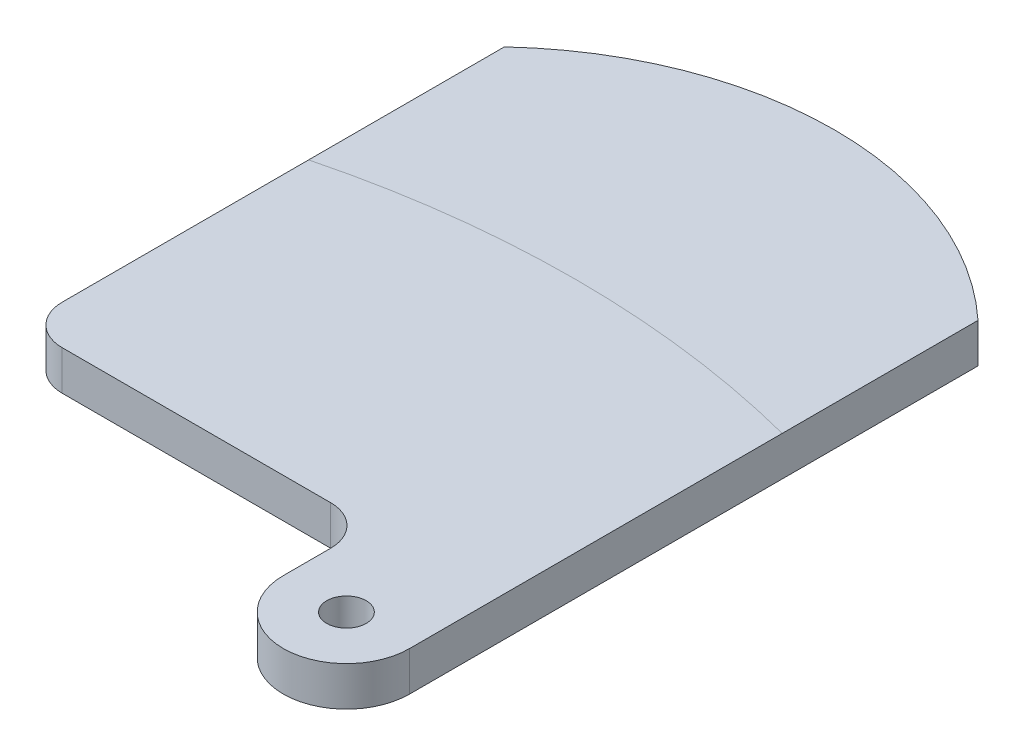
SolidWorks part; units mm, degrees
material "7075-T6 (SN)"
ref_plane "Front Plane" through (0, 0, 0) normal (0, 0, 1) x (1, 0, 0)
ref_plane "Top Plane" through (0, 0, 0) normal (0, 1, 0) x (1, 0, 0)
ref_plane "Right Plane" through (0, 0, 0) normal (1, 0, 0) x (0, 0, -1)
sketch "Sketch1" plane through (0, 0, 0) normal (0, 1, 0) x (1, 0, 0)
  line L10 (-19.05, 10.16) -> (-19.05, 45.72)
  line L12 (19.05, 10.16) -> (19.05, 45.72)
  line L14 (19.05, 10.16) -> (19.05, 0)
  line L15 (8.89, 0) -> (8.89, 3.81)
  line L16 (5.715, 6.985) -> (-15.875, 6.985)
  line L17 (-19.05, 45.72) -> (19.05, 45.72) construction
  arc A7 (-19.05, 45.72) -> (19.05, 45.72) centre (0, 25.2813) cw
  arc A12 (19.05, 0) -> (8.89, 0) centre (13.97, 0) cw
  arc A13 (8.89, 3.81) -> (5.715, 6.985) centre (5.715, 3.81) ccw
  arc A14 (-15.875, 6.985) -> (-19.05, 10.16) centre (-15.875, 10.16) cw
  point P7 (0, 45.72)
  dimension "D10" = 27.94
  dimension "D4" = 5.08
  dimension "D5" = 3.175
  dimension "D2" = 38.1
  dimension "D3" = 45.72
  dimension "D6" = 35.56
extrude "Boss-Extrude1" add sketch "Sketch1" along normal blind 3.175
hole_wizard "1/8 (0.1250) Dowel Hole1" positions "Sketch2" profile "Sketch3" hole size "1/8" standard "ANSI Inch" end condition through all
sketch "Sketch2" plane through (0, 3.175, 0) normal (0, 1, 0) x (1, 0, 0)
  point P0 (13.97, 0)
sketch "Sketch3" plane through (13.97, 3.175, 0) normal (1, 0, 0) x (0, 0, 1)
  line L0 (0, 0) -> (0, 3.175)
  line L1 (0, 3.175) -> (1.5875, 3.175)
  line L2 (1.5875, 3.175) -> (1.5875, 0)
  line L5 (1.5875, 0) -> (0, 0)
  line L11 (0, -6.35) -> (0, 107.95) construction
  dimension "Thru Hole Dia." = 3.175
  dimension "Thru Hole Depth" = 3.175
sketch "Sketch4" [suppressed] plane through (0, 0, 0) normal (0, -1, 0) x (1, 0, 0)
  line L1 (-19.05, -45.72) -> (-12.7, -45.72)
  line L2 (-19.05, -45.72) -> (-19.05, -58.42)
  line L3 (-19.05, -58.42) -> (-12.7, -58.42)
  line L4 (-12.7, -45.72) -> (-12.7, -58.42)
  dimension "D1" = 12.7
  dimension "D2" = 6.35
extrude "Boss-Extrude2" [suppressed] add sketch "Sketch4" against normal blind 1.27
sketch "Sketch5" [suppressed] plane through (0, 1.27, 0) normal (0, 1, 0) x (1, 0, 0)
  line L0 (-19.05, 58.42) -> (-12.7, 58.42)
  line L1 (-12.7, 58.42) -> (-12.7, 54.3806)
  line L2 (-12.7, 58.42) -> (-12.7, 50.1681) construction
  line L3 (-19.05, 58.42) -> (-19.05, 50.6813)
  line L4 (-19.05, 45.72) -> (-19.05, 58.42) construction
  arc A0 (19.05, 45.72) -> (-19.05, 45.72) centre (0, 25.2813) ccw construction
  arc A1 (19.05, 45.72) -> (-19.05, 45.72) centre (0, 25.2813) ccw
  arc A2 (-12.7, 54.3806) -> (-19.05, 50.6813) centre (0, 25.2813) ccw
  arc A3 (21.6477, 48.5071) -> (-21.6477, 48.5071) centre (0, 25.2813) ccw construction
  line M1 (-19.05, 58.42) -> (-19.05, 45.72)
  line M3 (-12.7, 50.1681) -> (-12.7, 58.42)
  line M4 (-12.7, 58.42) -> (-19.05, 58.42)
  dimension "D1" = 3.81
extrude "Boss-Extrude3" [suppressed] add sketch "Sketch5" along normal up to surface (1.905 mm away) contours A2 M3 M4 M1
hole_wizard "1/8 (0.1250) Dowel Hole2" positions "Sketch6" profile "Sketch7" hole size "1/8" standard "ANSI Inch" end condition through all
sketch "Sketch6" plane through (0, 3.175, 0) normal (0, 1, 0) x (1, 0, 0)
  line L0 (-16.3067, 55.6767) -> (-16.3067, 58.42) construction
  line L1 (-19.05, 58.42) -> (-12.7, 58.42) construction
  line L3 (-16.3067, 55.6767) -> (-19.05, 55.6767) construction
  line L4 (-19.05, 50.6813) -> (-19.05, 58.42) construction
  line L6 (-16.3067, 55.6767) -> (-15.0098, 53.2593) construction
  line L8 (-15.0098, 53.2593) -> (-17.248, 52.0585) construction
  arc A0 (-12.7, 54.3806) -> (-19.05, 50.6813) centre (0, 25.2813) ccw construction
  point P0 (-16.3067, 55.6767)
  dimension "D1" = 2.54
sketch "Sketch7" plane through (-16.3067, 3.175, -55.6767) normal (1, 0, 0) x (0, 0, 1)
  line L0 (0, 0) -> (0, 3.175)
  line L1 (0, 3.175) -> (1.5875, 3.175)
  line L2 (1.5875, 3.175) -> (1.5875, 0)
  line L5 (1.5875, 0) -> (0, 0)
  line L11 (0, -6.35) -> (0, 107.95) construction
  dimension "Thru Hole Dia." = 3.175
  dimension "Thru Hole Depth" = 3.175
fillet "Fillet1" [suppressed] radius 3.175
fillet "Fillet2" [suppressed] radius 2.286
mirror "Mirror1" [suppressed] about plane through (0, 0, 0) normal (1, 0, 0)
sketch "Sketch8" plane through (0, 3.175, 0) normal (0, 1, 0) x (1, 0, 0)
  line L0 (-19.05, 45.72) -> (-19.05, 10.16) construction
  line L1 (19.05, 0) -> (19.05, 45.72) construction
  arc A0 (-19.05, 29.9736) -> (19.05, 29.9736) centre (0, -43.8067) cw
  arc A1 (19.05, 45.72) -> (-19.05, 45.72) centre (0, 25.2813) ccw construction
  point P9 (0, 32.3933)
  point P13 (0, 53.2213)
  dimension "D1" = 76.2
  dimension "D2" = 20.828
split line "Split Line1"
equation "\"atsFlapWidth\" = 1.5in"
equation "\"atsFlapThickness\" = 0.125in"
equation "\"D2@Sketch1\"=\"atsFlapWidth\""
equation "\"D4@Sketch1\"=0.2"
equation "\"D1@Boss-Extrude1\"=\"atsFlapThickness\""
